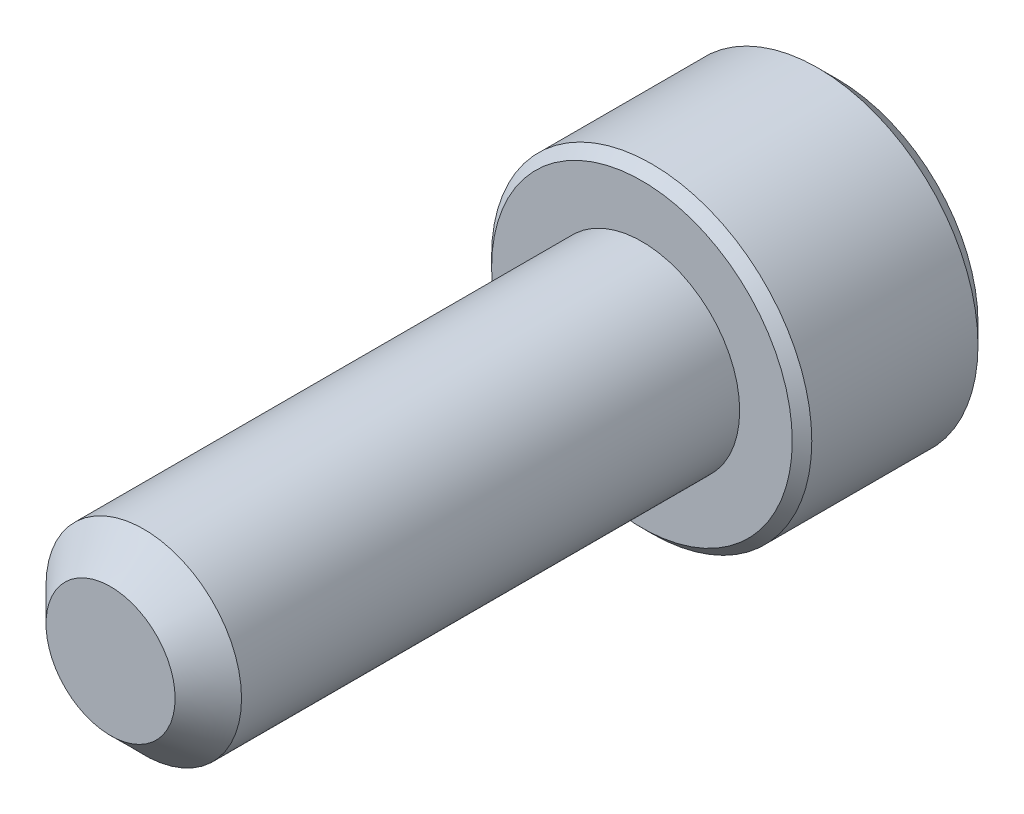
SolidWorks part; units mm, degrees
material "Plain Carbon Steel"
ref_plane "Front Plane" through (0, 0, 0) normal (0, 0, 1) x (1, 0, 0)
ref_plane "Top Plane" through (0, 0, 0) normal (0, 1, 0) x (1, 0, 0)
ref_plane "Right Plane" through (0, 0, 0) normal (1, 0, 0) x (0, 0, -1)
sketch "Sketch1" plane through (0, 0, 0) normal (0, 0, 1) x (1, 0, 0)
  line L0 (0, 1.7526) -> (0, -1.7526) construction
  circle A0 centre (0, 0) radius 1.7526
  dimension "OD" = 3.5052
extrude "Extrude1" add sketch "Sketch1" against normal blind 9.525
sketch "Sketch2" plane through (0, 0, 0) normal (0, 0, 1) x (1, 0, 0)
  circle A0 centre (0, 0) radius 1.7526 construction
  circle A1 centre (0, 0) radius 1.7526
curve "Helix/Spiral1" pitch 0.7937 height 10.3188 turns 13 parameters "pitch"=0.7937
chamfer "Chamfer3" distance 0.5953 angle 45 1 edges at (1.7526, 0, 0)
sketch "Sketch3" plane through (0, 0, 0) normal (1, 0, 0) x (0, 0, -1)
  line L0 (-0.6945, 1.7526) -> (-0.3969, 1.237)
  line L1 (-0.3969, 1.237) -> (-0.2977, 1.237)
  line L2 (-0.2977, 1.237) -> (0, 1.7526)
  line L3 (-0.6945, 1.7526) -> (0, 1.7526)
  line L4 (-0.3473, 1.7526) -> (-0.3473, 1.237) construction
  line L5 (-0.5457, 1.4948) -> (-0.1488, 1.4948) construction
  line L6 (0, 1.7526) -> (0, -1.7526) construction
  dimension "D1" = 0.0992
  dimension "D2" = 0.3969
  dimension "D3" = 60
sketch "Sketch6" plane through (0, 0, -9.525) normal (0, 0, -1) x (-1, 0, 0)
  circle A0 centre (0, 0) radius 2.8702
  dimension "head dia" = 5.7404
extrude "Extrude2" add sketch "Sketch6" along normal blind 3.5052
sketch "Sketch7" plane through (0, 0, -13.0302) normal (0, 0, -1) x (-1, 0, 0)
  line L1 (0, 1.604) -> (-1.3891, 0.802)
  line L2 (-1.3891, 0.802) -> (-1.3891, -0.802)
  line L3 (-1.3891, -0.802) -> (0, -1.604)
  line L4 (0, -1.604) -> (1.3891, -0.802)
  line L5 (1.3891, -0.802) -> (1.3891, 0.802)
  line L6 (1.3891, 0.802) -> (0, 1.604)
  circle A0 centre (0, 0) radius 1.3891 construction
  dimension "hex dia" = 2.7781
extrude "Cut-Extrude1" cut sketch "Sketch7" against normal blind 2.0836
sketch "Sketch8" plane through (0, 0, -13.0302) normal (0, 0, -1) x (-1, 0, 0)
  circle A0 centre (0, 0) radius 1.604
extrude "Cut-Extrude2" cut sketch "Sketch8" against normal blind 0.3505 draft 45
chamfer "Chamfer1" distance 0.3505 angle 45 1 edges at (-2.8702, 0, -13.0302)
chamfer "Chamfer2" distance 0.1753 angle 45 1 edges at (-2.8702, 0, -9.525)
sketch "Sketch9" plane through (0, 0, 0) normal (1, 0, 0) x (0, 0, -1)
  line L0 (0, 1.7526) -> (0, -1.7526) construction
  line L1 (4.3656, 1.7526) -> (4.3656, -1.7526) construction
  line L2 (9.525, 2.8702) -> (9.525, -2.8702) construction
  line L3 (13.0302, 2.8702) -> (13.0302, -2.8702) construction
  line L4 (13.0302, 0) -> (0, 0) construction
  dimension "D1" = 4.3656
  dimension "D2" = 3.5052
  dimension "D3" = 5.7404
  dimension "D4" = 9.525
equation "\"D3@Helix/Spiral1\" = \"screw length@Extrude1\"+\"pitch@Helix/Spiral1\""
equation "\"D1@Sketch3\" = \"pitch@Helix/Spiral1\"*.125"
equation "\"D2@Sketch3\" = \"pitch@Helix/Spiral1\"*.5"
equation "\"D1@Cut-Extrude1\" = \"hex dia@Sketch7\"*.75"
equation "\"D1@Chamfer1\" = \"head depth@Extrude2\"/10"
equation "\"D1@Sketch9\" = \"pitch@Helix/Spiral1\"*5.5"
equation "\"D1@Chamfer2\" = \"D1@Chamfer1\"/2"
equation "\"D1@Cut-Extrude2\" = \"D1@Chamfer2\"*2"
equation "\"D1@Chamfer3\" = \"pitch@Helix/Spiral1\"*.750"
equation "\"D2@Sketch9\" = \"head depth@Extrude2\""
equation "\"D3@Sketch9\" = \"head dia@Sketch6\""
equation "\"D4@Sketch9\" = \"screw length@Extrude1\""
